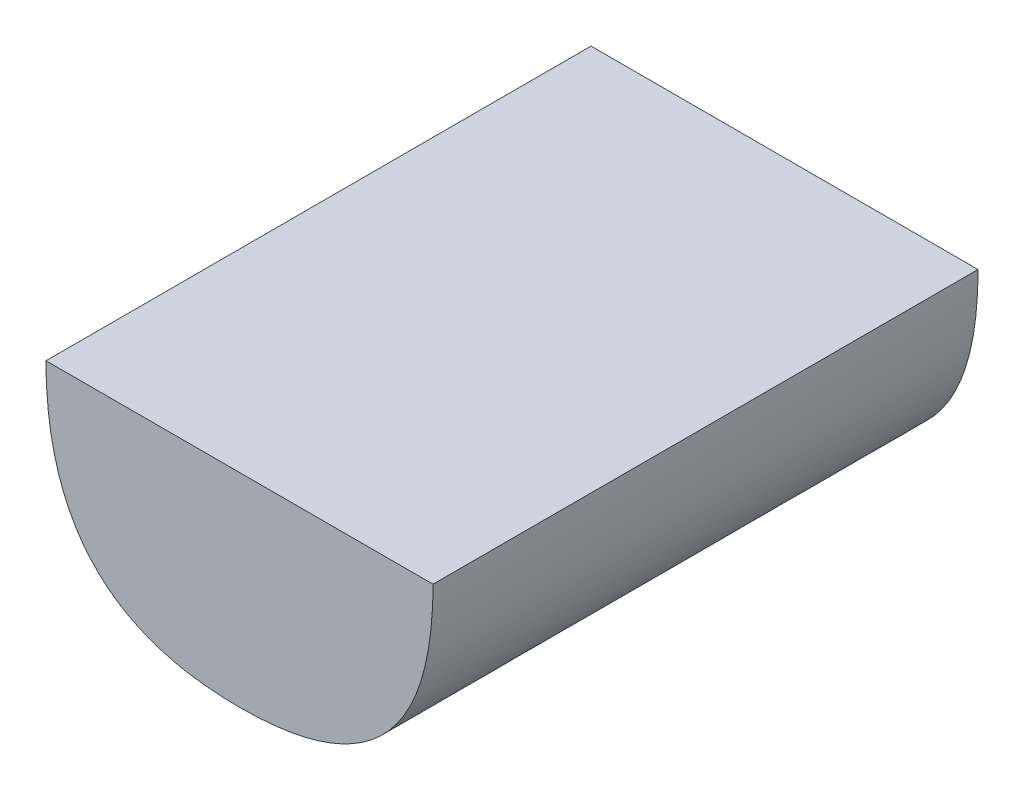
SolidWorks part; units mm, degrees
ref_plane "Front Plane" through (0, 0, 0) normal (0, 0, 1) x (1, 0, 0)
ref_plane "Top Plane" through (0, 0, 0) normal (0, 1, 0) x (1, 0, 0)
ref_plane "Right Plane" through (0, 0, 0) normal (1, 0, 0) x (0, 0, -1)
sketch "Sketch1" plane through (0, 0, 0) normal (0, 0, 1) x (1, 0, 0)
  line L0 (0, 0) -> (0, 739.4116) construction
  line L5 (-302.357, 317.813) -> (302.357, 317.813)
  conic Q0 (0, 0) -> (302.357, 317.813) control (302.357, -0.0664) rho 0.504796
  conic Q1 (0, 0) -> (-302.357, 317.813) control (-302.357, -0.0664) rho 0.504796
extrude "Boss-Extrude1" add sketch "Sketch1" against normal blind 851.662 contours Q0 L5 Q1
